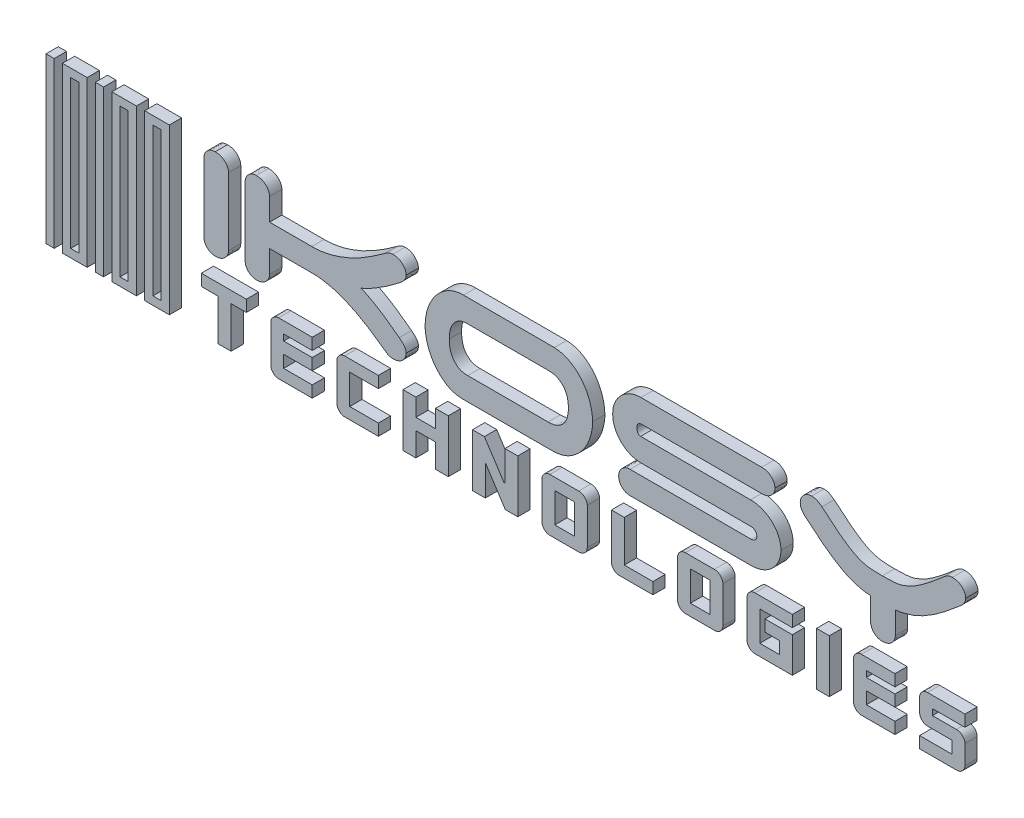
SolidWorks part; units mm, degrees
other "Symbol Extrude 1-1"
other "Symbol Extrude 2-0"
other "Symbol Extrude 3-1"
other "Text Extrude I"
other "Text Extrude K"
other "Text Extrude O"
other "Text Extrude S"
other "Text Extrude Y" parameters "D1"=6.2983, "D2"=2.0167, "D3"=11.6967, "D4"=11.6967, "D5"=1.4517, "D6"=1.4517, "D7"=14.1973, "D8"=14.1973, "D9"=30.15, "D10"=33.5, "D11"=33.5, "D12"=33.5, "D13"=30.15
ref_plane "Front Plane" through (0, 0, 0) normal (0, 0, 1) x (1, 0, 0)
ref_plane "Top Plane" through (0, 0, 0) normal (0, 1, 0) x (1, 0, 0)
ref_plane "Right Plane" through (0, 0, 0) normal (1, 0, 0) x (0, 0, -1)
sketch "Insertion Point Sketch" plane through (0, 0, 0) normal (0, 0, 1) x (1, 0, 0)
  line L0 (-3.25, -3.25) -> (-3.25, 0) construction
  line L1 (-3.25, -3.25) -> (0, -3.25) construction
  dimension "D1" = 3.25
  dimension "D2" = 3.25
ref_plane "3D Printing Base Plane" through (0, 0, -4) normal (0, 0, 1) x (1, 0, 0)
sketch "3D Printing Origin Sketch" plane through (0, 0, -4) normal (0, 0, 1) x (1, 0, 0)
  point P0 (-24.5, -6.5)
  dimension "D1" = 21.25
  dimension "D2" = 3.25
sketch "Symbol Sketch" plane through (0, 0, 0) normal (0, 0, 1) x (1, 0, 0)
  line L1 (-3.25, 30.25) -> (-1.575, 30.25)
  line L2 (-3.25, 30.25) -> (-3.25, -3.25)
  line L3 (-3.25, -3.25) -> (-1.575, -3.25)
  line L4 (-1.575, 30.25) -> (-1.575, -3.25)
  line L5 (1.775, 28.575) -> (3.45, 28.575)
  line L6 (1.775, 28.575) -> (1.775, -1.575)
  line L7 (1.775, -1.575) -> (3.45, -1.575)
  line L8 (3.45, 28.575) -> (3.45, -1.575)
  line L9 (0.1, 30.25) -> (5.125, 30.25)
  line L10 (0.1, 30.25) -> (0.1, -3.25)
  line L11 (0.1, -3.25) -> (5.125, -3.25)
  line L12 (5.125, 30.25) -> (5.125, -3.25)
  line L13 (6.8, 30.25) -> (8.475, 30.25)
  line L14 (6.8, 30.25) -> (6.8, -3.25)
  line L15 (6.8, -3.25) -> (8.475, -3.25)
  line L16 (8.475, 30.25) -> (8.475, -3.25)
  line L17 (10.15, 30.25) -> (15.175, 30.25)
  line L18 (10.15, 30.25) -> (10.15, -3.25)
  line L19 (10.15, -3.25) -> (15.175, -3.25)
  line L20 (15.175, 30.25) -> (15.175, -3.25)
  line L21 (11.825, 28.575) -> (13.5, 28.575)
  line L22 (11.825, 28.575) -> (11.825, -1.575)
  line L23 (11.825, -1.575) -> (13.5, -1.575)
  line L24 (13.5, 28.575) -> (13.5, -1.575)
  line L25 (16.85, 30.25) -> (21.875, 30.25)
  line L26 (16.85, 30.25) -> (16.85, -3.25)
  line L27 (16.85, -3.25) -> (21.875, -3.25)
  line L28 (21.875, 30.25) -> (21.875, -3.25)
  line L29 (18.525, 28.575) -> (20.2, 28.575)
  line L30 (18.525, 28.575) -> (18.525, -1.575)
  line L31 (18.525, -1.575) -> (20.2, -1.575)
  line L32 (20.2, 28.575) -> (20.2, -1.575)
  dimension "D1" = 1.675
  dimension "D2" = 1.675
  dimension "D3" = 1.675
  dimension "D4" = 1.675
  dimension "D5" = 1.675
  dimension "D6" = 1.675
  dimension "D7" = 1.675
  dimension "D8" = 33.5
  dimension "D9" = 1.675
  dimension "D10" = 1.675
  dimension "D11" = 1.675
  dimension "D12" = 1.675
  dimension "D13" = 1.675
extrude "Symbol Extrude" add sketch "Symbol Sketch" along normal blind 2.5
sketch "Text Sketch" plane through (0, 0, 0) normal (0, 0, 1) x (1, 0, 0)
  line L0 (21.875, 30.25) -> (184.25, 30.25) construction
  line L1 (184.25, 30.25) -> (184.25, -3.25) construction
  text T0 "ikosy" font "Space Age" height 18.425
  text T1 "TECHNOLOGIES" font "Alien Encounters Solid" height 10.75
  dimension "D3" = 1.1
  dimension "D2" = 12.075
  dimension "D1" = 30.125
  dimension "D4" = 187.5
extrude "Text Extrude" add sketch "Text Sketch" along normal blind 2.5 separate body
equation "\"Logo Height\"= \"Total Height\" - 2 * \"Border\""
equation "\"Total Height\"= 40mm"
equation "\"Border\"= 3.25mm"
equation "\"Symbol Width\"= \"Logo Height\" * 0.75"
equation "\"Line Width\"= \"Symbol Width\" / 15"
equation "\"D2@Symbol Sketch\" = \"Line Width\""
equation "\"D1@Symbol Sketch\" = \"Line Width\""
equation "\"D3@Symbol Sketch\" = \"Line Width\""
equation "\"D4@Symbol Sketch\" = \"Line Width\""
equation "\"D5@Symbol Sketch\" = \"Line Width\""
equation "\"D6@Symbol Sketch\" = \"Line Width\""
equation "\"D7@Symbol Sketch\" = \"Line Width\""
equation "\"D8@Symbol Sketch\" = \"Logo Height\""
equation "\"D9@Symbol Sketch\" = \"Line Width\""
equation "\"D10@Symbol Sketch\" = \"Line Width\""
equation "\"D11@Symbol Sketch\" = \"Line Width\""
equation "\"D12@Symbol Sketch\" = \"Line Width\""
equation "\"D13@Symbol Sketch\" = \"Line Width\""
equation "\"Ikosy X Position\"= \"Symbol Width\" + 5mm"
equation "\"Ikosy Y Position\"= ( 1 - 0.55 ) * \"Logo Height\" - 3"
equation "\"D1@Insertion Point Sketch\" = \"Border\""
equation "\"D2@Insertion Point Sketch\" = \"Border\""
equation "\"D2@Text Sketch\"=\"Ikosy Y Position\""
equation "\"D1@Text Sketch\"=\"Ikosy X Position\""
